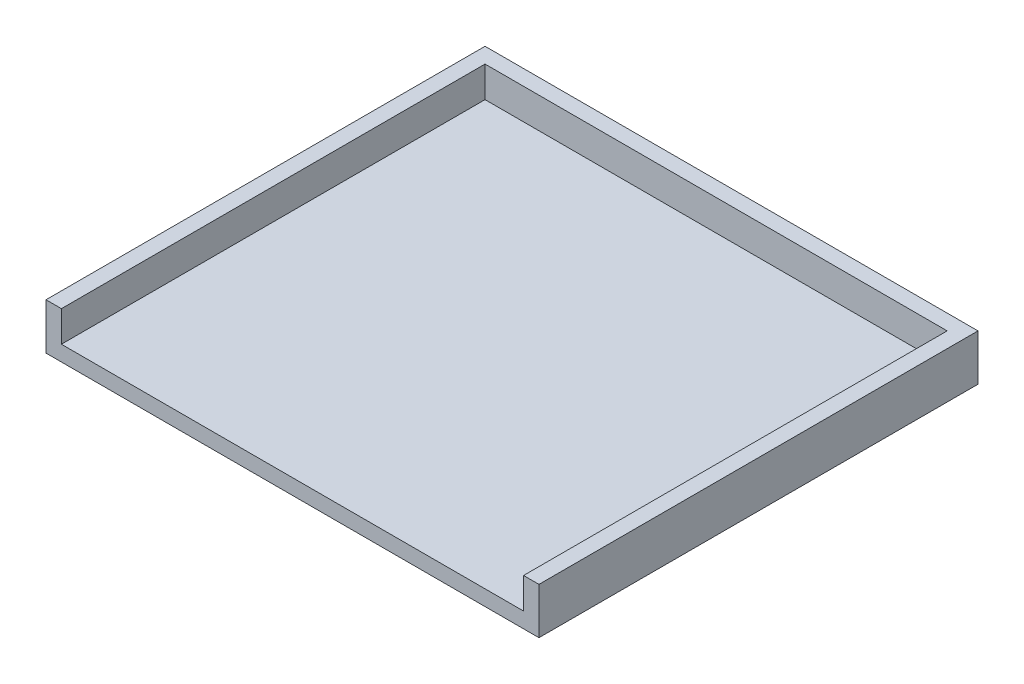
SolidWorks part; units mm, degrees
ref_plane "Front Plane" through (0, 0, 0) normal (0, 0, 1) x (1, 0, 0)
ref_plane "Top Plane" through (0, 0, 0) normal (0, 1, 0) x (1, 0, 0)
ref_plane "Right Plane" through (0, 0, 0) normal (1, 0, 0) x (0, 0, -1)
sketch "Sketch1" plane through (0, 0, 0) normal (0, 1, 0) x (1, 0, 0)
  line L1 (0, 0) -> (1280, 0)
  line L2 (0, 0) -> (0, -1140)
  line L3 (0, -1140) -> (1280, -1140)
  line L4 (1280, 0) -> (1280, -1140)
  dimension "D1" = 1140
  dimension "D2" = 1280
extrude "Boss-Extrude1" add sketch "Sketch1" along normal blind 40
sketch "Sketch2" plane through (0, 40, 0) normal (0, 1, 0) x (1, 0, 0)
  line L0 (0, -1140) -> (1280, -1140) construction
  line L1 (1280, 0) -> (1240, 0)
  line L2 (1280, 0) -> (1280, -1140)
  line L3 (1280, -1140) -> (1240, -1140)
  line L4 (1240, 0) -> (1240, -1140)
  line L5 (640, 0) -> (640, -1140) construction
  line L6 (1280, 0) -> (0, 0) construction
  line L7 (40, 0) -> (40, -1140)
  line L8 (0, -1140) -> (40, -1140)
  line L9 (0, 0) -> (0, -1140)
  line L10 (0, 0) -> (40, 0)
  dimension "D1" = 40
extrude "Boss-Extrude2" add sketch "Sketch2" along normal blind 80
sketch "Sketch3" plane through (0, 40, 0) normal (0, 1, 0) x (1, 0, 0)
  line L0 (1240, 0) -> (1240, -1140) construction
  line L1 (40, 0) -> (1240, 0)
  line L2 (40, 0) -> (40, -40)
  line L3 (40, -40) -> (1240, -40)
  line L4 (1240, 0) -> (1240, -40)
  dimension "D1" = 40
extrude "Boss-Extrude3" add sketch "Sketch3" along normal blind 80
